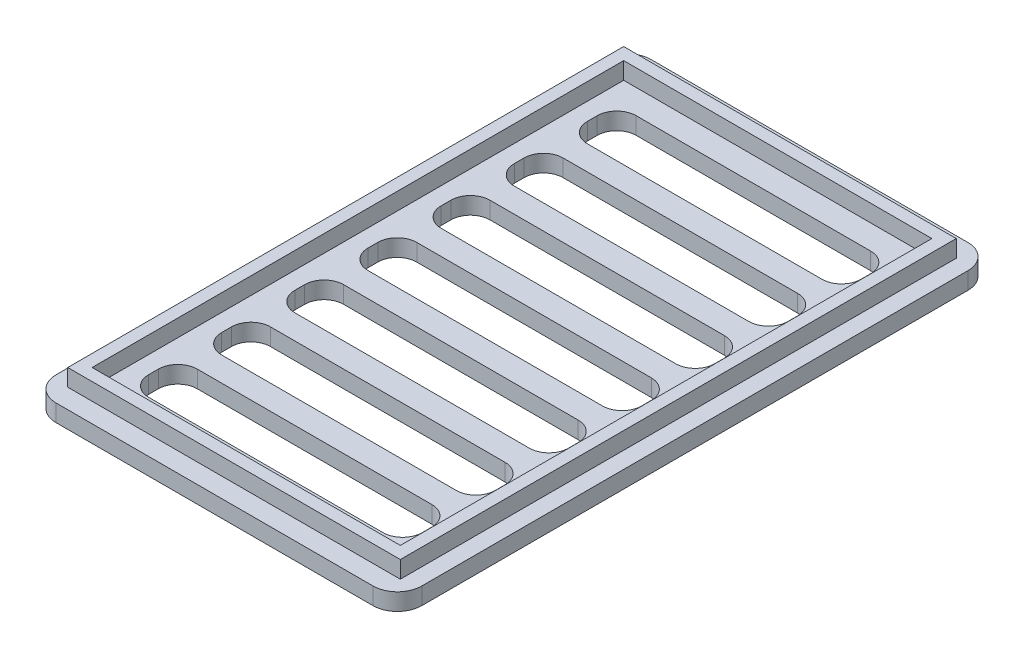
SolidWorks part; units mm, degrees
ref_plane "Front Plane" through (0, 0, 0) normal (0, 0, 1) x (1, 0, 0)
ref_plane "Top Plane" through (0, 0, 0) normal (0, 1, 0) x (1, 0, 0)
ref_plane "Right Plane" through (0, 0, 0) normal (1, 0, 0) x (0, 0, -1)
sketch "Sketch1" plane through (0, 0, 0) normal (0, 1, 0) x (1, 0, 0)
  line L1 (-175.6426, -124.0686) -> (-138.1426, -124.0686)
  line L2 (-175.6426, -124.0686) -> (-175.6426, -63.0686)
  line L3 (-175.6426, -63.0686) -> (-138.1426, -63.0686)
  line L4 (-138.1426, -124.0686) -> (-138.1426, -63.0686)
  dimension "D1" = 61
  dimension "D2" = 37.5
extrude "Boss-Extrude1" add sketch "Sketch1" along normal blind 1.75
sketch "Sketch2" plane through (0, 1.75, 0) normal (0, 1, 0) x (1, 0, 0)
  line L0 (-138.1426, -124.0686) -> (-138.1426, -63.0686) construction
  line L1 (-173.9426, -122.0686) -> (-139.8426, -122.0686)
  line L2 (-173.9426, -122.0686) -> (-173.9426, -65.0686)
  line L3 (-173.9426, -65.0686) -> (-139.8426, -65.0686)
  line L4 (-139.8426, -122.0686) -> (-139.8426, -65.0686)
  line L6 (-175.6426, -124.0686) -> (-138.1426, -124.0686) construction
  dimension "D1" = 57
  dimension "D2" = 34.1
  dimension "D3" = 1.7
  dimension "D4" = 2
extrude "Boss-Extrude2" add sketch "Sketch2" along normal blind 1.75
sketch "Sketch3" plane through (0, 3.5, 0) normal (0, 1, 0) x (1, 0, 0)
  line L0 (-139.8426, -65.0686) -> (-173.9426, -65.0686) construction
  line L1 (-172.6926, -120.8186) -> (-141.0926, -120.8186)
  line L2 (-172.6926, -120.8186) -> (-172.6926, -66.3186)
  line L3 (-172.6926, -66.3186) -> (-141.0926, -66.3186)
  line L4 (-141.0926, -120.8186) -> (-141.0926, -66.3186)
  line L5 (-139.8426, -122.0686) -> (-139.8426, -65.0686) construction
  line L6 (-173.9426, -122.0686) -> (-139.8426, -122.0686) construction
  line L7 (-173.9426, -65.0686) -> (-173.9426, -122.0686) construction
  dimension "D1" = 1.25
  dimension "D2" = 1.25
  dimension "D3" = 1.25
  dimension "D4" = 1.25
extrude "Cut-Extrude1" cut sketch "Sketch3" against normal blind 1.75
sketch "Sketch4" plane through (0, 1.75, 0) normal (0, 1, 0) x (1, 0, 0)
  line L0 (-172.6926, -120.8186) -> (-141.0926, -120.8186) construction
  line L1 (-168.906, -118.8186) -> (-144.861, -118.8186)
  line L2 (-170.906, -116.8186) -> (-170.906, -115.8186)
  line L3 (-168.906, -113.8186) -> (-144.861, -113.8186)
  line L4 (-142.861, -116.8186) -> (-142.861, -115.8186)
  line L5 (-168.906, -103.8186) -> (-144.861, -103.8186)
  line L6 (-170.906, -101.8186) -> (-170.906, -100.8186)
  line L7 (-168.906, -98.8186) -> (-144.861, -98.8186)
  line L8 (-142.861, -101.8186) -> (-142.861, -100.8186)
  line L9 (-168.906, -96.3186) -> (-144.861, -96.3186)
  line L10 (-170.906, -94.3186) -> (-170.906, -93.3186)
  line L11 (-168.906, -91.3186) -> (-144.861, -91.3186)
  line L12 (-142.861, -94.3186) -> (-142.861, -93.3186)
  line L13 (-168.906, -81.3186) -> (-144.861, -81.3186)
  line L14 (-170.906, -79.3186) -> (-170.906, -78.3186)
  line L15 (-168.906, -76.3186) -> (-144.861, -76.3186)
  line L16 (-142.861, -79.3186) -> (-142.861, -78.3186)
  line L17 (-168.906, -111.3186) -> (-144.861, -111.3186)
  line L18 (-170.906, -109.3186) -> (-170.906, -108.3186)
  line L19 (-168.906, -106.3186) -> (-144.861, -106.3186)
  line L20 (-142.861, -109.3186) -> (-142.861, -108.3186)
  line L21 (-168.906, -88.8186) -> (-144.861, -88.8186)
  line L22 (-170.906, -86.8186) -> (-170.906, -85.8186)
  line L23 (-168.906, -83.8186) -> (-144.861, -83.8186)
  line L24 (-142.861, -86.8186) -> (-142.861, -85.8186)
  line L26 (-168.906, -73.8186) -> (-144.861, -73.8186)
  line L27 (-170.906, -71.8186) -> (-170.906, -70.8186)
  line L28 (-168.906, -68.8186) -> (-144.861, -68.8186)
  line L29 (-142.861, -71.8186) -> (-142.861, -70.8186)
  arc A0 (-144.861, -118.8186) -> (-142.861, -116.8186) centre (-144.861, -116.8186) ccw
  arc A1 (-144.861, -113.8186) -> (-142.861, -115.8186) centre (-144.861, -115.8186) cw
  arc A2 (-144.861, -111.3186) -> (-142.861, -109.3186) centre (-144.861, -109.3186) ccw
  arc A3 (-144.861, -106.3186) -> (-142.861, -108.3186) centre (-144.861, -108.3186) cw
  arc A4 (-144.861, -103.8186) -> (-142.861, -101.8186) centre (-144.861, -101.8186) ccw
  arc A5 (-144.861, -98.8186) -> (-142.861, -100.8186) centre (-144.861, -100.8186) cw
  arc A6 (-144.861, -96.3186) -> (-142.861, -94.3186) centre (-144.861, -94.3186) ccw
  arc A7 (-144.861, -91.3186) -> (-142.861, -93.3186) centre (-144.861, -93.3186) cw
  arc A8 (-144.861, -88.8186) -> (-142.861, -86.8186) centre (-144.861, -86.8186) ccw
  arc A9 (-144.861, -83.8186) -> (-142.861, -85.8186) centre (-144.861, -85.8186) cw
  arc A10 (-144.861, -81.3186) -> (-142.861, -79.3186) centre (-144.861, -79.3186) ccw
  arc A11 (-144.861, -76.3186) -> (-142.861, -78.3186) centre (-144.861, -78.3186) cw
  arc A12 (-144.861, -73.8186) -> (-142.861, -71.8186) centre (-144.861, -71.8186) ccw
  arc A13 (-144.861, -68.8186) -> (-142.861, -70.8186) centre (-144.861, -70.8186) cw
  arc A14 (-170.906, -70.8186) -> (-168.906, -68.8186) centre (-168.906, -70.8186) cw
  arc A15 (-168.906, -73.8186) -> (-170.906, -71.8186) centre (-168.906, -71.8186) cw
  arc A16 (-170.906, -78.3186) -> (-168.906, -76.3186) centre (-168.906, -78.3186) cw
  arc A17 (-168.906, -81.3186) -> (-170.906, -79.3186) centre (-168.906, -79.3186) cw
  arc A18 (-170.906, -85.8186) -> (-168.906, -83.8186) centre (-168.906, -85.8186) cw
  arc A19 (-168.906, -88.8186) -> (-170.906, -86.8186) centre (-168.906, -86.8186) cw
  arc A20 (-170.906, -93.3186) -> (-168.906, -91.3186) centre (-168.906, -93.3186) cw
  arc A21 (-168.906, -96.3186) -> (-170.906, -94.3186) centre (-168.906, -94.3186) cw
  arc A22 (-170.906, -100.8186) -> (-168.906, -98.8186) centre (-168.906, -100.8186) cw
  arc A23 (-168.906, -103.8186) -> (-170.906, -101.8186) centre (-168.906, -101.8186) cw
  arc A24 (-170.906, -108.3186) -> (-168.906, -106.3186) centre (-168.906, -108.3186) cw
  arc A25 (-168.906, -111.3186) -> (-170.906, -109.3186) centre (-168.906, -109.3186) cw
  arc A26 (-170.906, -115.8186) -> (-168.906, -113.8186) centre (-168.906, -115.8186) cw
  arc A27 (-168.906, -118.8186) -> (-170.906, -116.8186) centre (-168.906, -116.8186) cw
  point P60 (-170.906, -68.8186)
  point P63 (-170.906, -73.8186)
  point P66 (-170.906, -76.3186)
  point P69 (-170.906, -81.3186)
  point P72 (-170.906, -83.8186)
  point P75 (-170.906, -88.8186)
  point P78 (-170.906, -91.3186)
  point P81 (-170.906, -96.3186)
  point P84 (-170.906, -98.8186)
  point P87 (-170.906, -103.8186)
  point P90 (-170.906, -106.3186)
  point P93 (-170.906, -111.3186)
  point P96 (-170.906, -113.8186)
  point P99 (-170.906, -118.8186)
  dimension "D15" = 2
  dimension "D1" = 5
  dimension "D2" = 5
  dimension "D3" = 5
  dimension "D4" = 5
  dimension "D5" = 5
  dimension "D6" = 5
  dimension "D7" = 2.5
  dimension "D8" = 2.5
  dimension "D9" = 2.5
  dimension "D10" = 2.5
  dimension "D11" = 2.5
  dimension "D12" = 2
  dimension "D13" = 5
  dimension "D14" = 2.5
extrude "Cut-Extrude3" cut sketch "Sketch4" against normal blind 1.75
fillet "Fillet1" radius 2.5 1 edges at (-138.1426, 0.875, 63.0686)
fillet "Fillet2" radius 2.5 1 edges at (-175.6426, 0.875, 63.0686)
fillet "Fillet3" radius 2.5 1 edges at (-175.6426, 0.875, 124.0686)
fillet "Fillet4" radius 2.5 1 edges at (-138.1426, 0.875, 124.0686)
